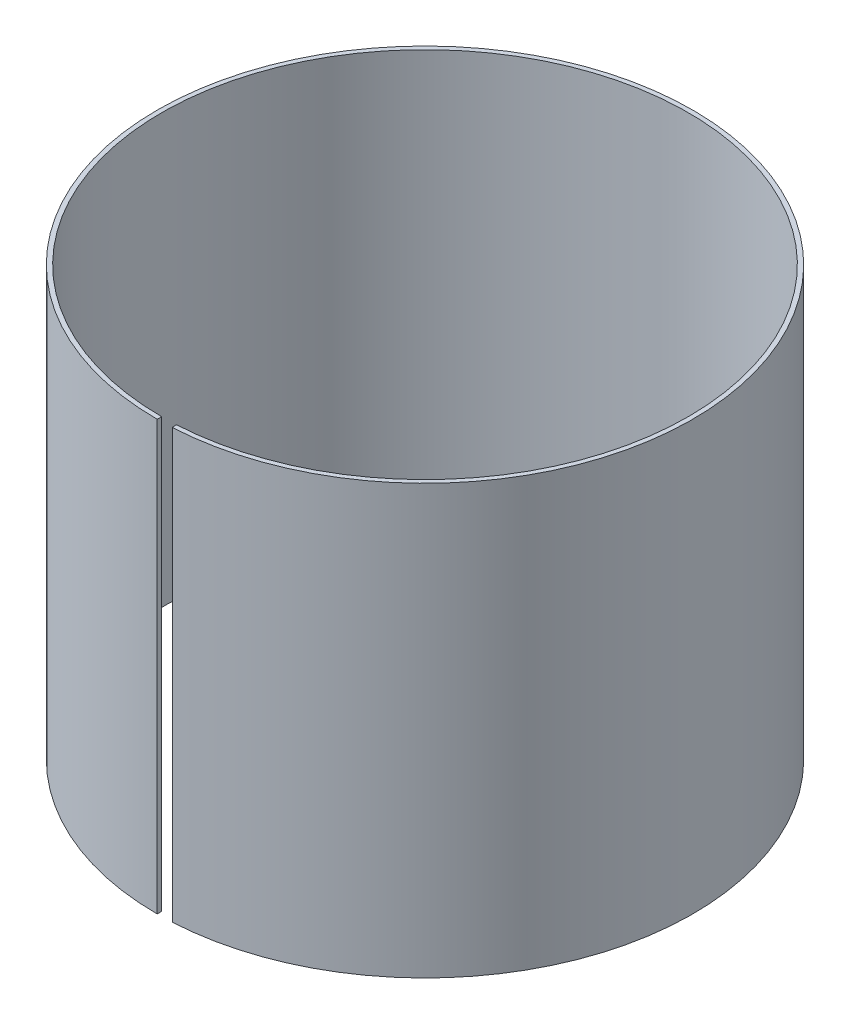
SolidWorks part; units mm, degrees
ref_plane "Front Plane" through (0, 0, 0) normal (0, 0, 1) x (1, 0, 0)
ref_plane "Top Plane" through (0, 0, 0) normal (0, 1, 0) x (1, 0, 0)
ref_plane "Right Plane" through (0, 0, 0) normal (1, 0, 0) x (0, 0, -1)
sketch "Sketch79" plane through (0, 0, 0) normal (0, 1, 0) x (1, 0, 0)
  arc A0 (0, -29.5) -> (1.6121, -29.4559) centre (0, 0) cw
extrude "Extrude-Thin2" add sketch "Sketch79" along normal blind 48 thin thin type one direction reverse wall 0.5
